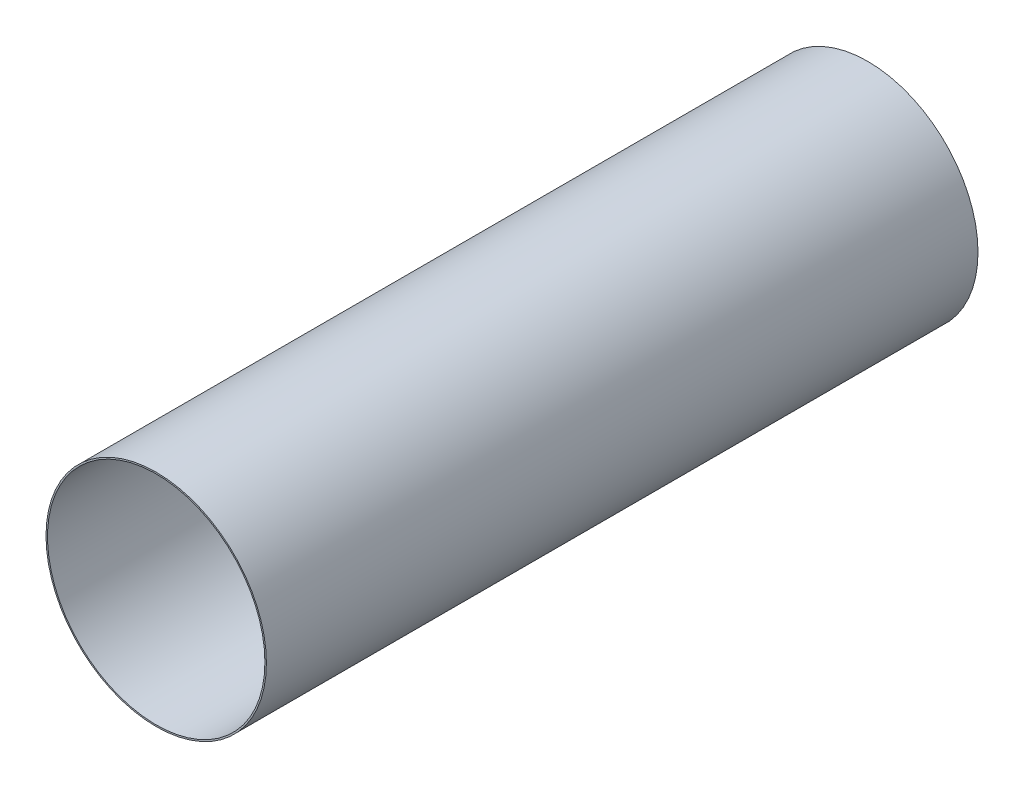
SolidWorks part; units mm, degrees
material "E-Glass Fiber"
ref_plane "Front Plane" through (0, 0, 0) normal (0, 0, 1) x (1, 0, 0)
ref_plane "Top Plane" through (0, 0, 0) normal (0, 1, 0) x (1, 0, 0)
ref_plane "Right Plane" through (0, 0, 0) normal (1, 0, 0) x (0, 0, -1)
sketch "Sketch1" plane through (0, 0, 0) normal (0, 0, 1) x (1, 0, 0)
  circle A0 centre (0, 0) radius 69.85
  circle A1 centre (0, 0) radius 70.8025
  dimension "D1" = 139.7
  dimension "D2" = 141.605
extrude "Extrude1" add sketch "Sketch1" along normal blind 457.2
